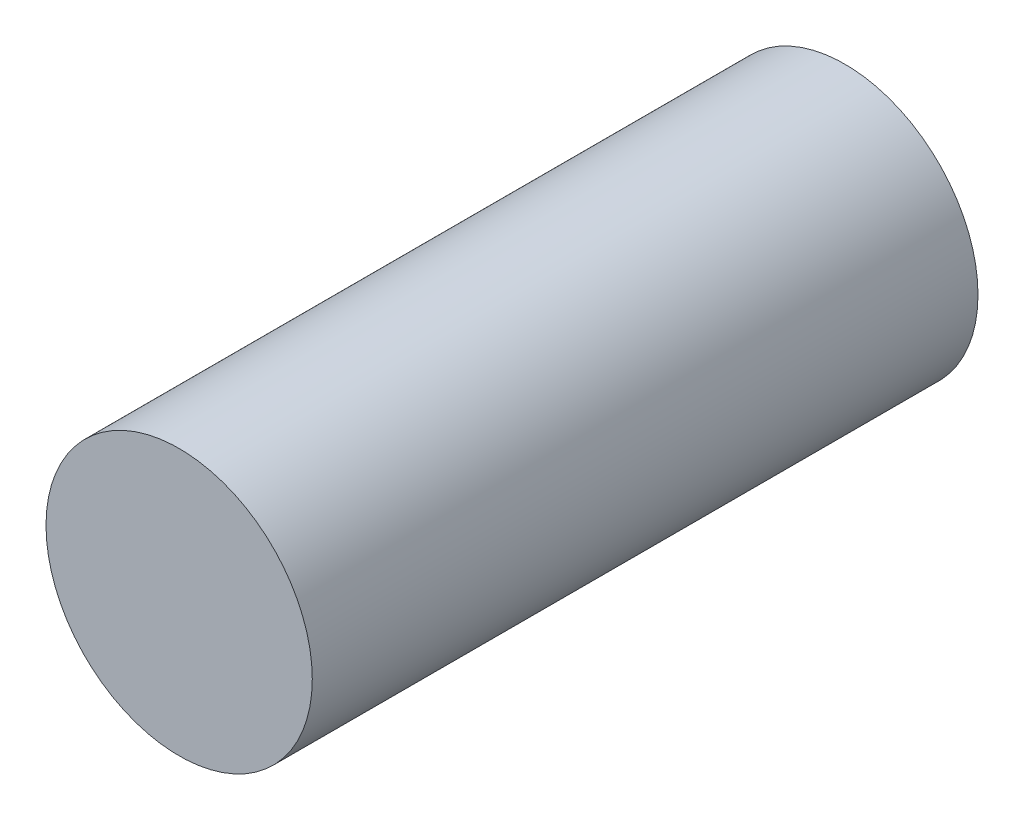
SolidWorks part; units mm, degrees
ref_plane "Plano frontal" through (0, 0, 0) normal (0, 0, 1) x (1, 0, 0)
ref_plane "Plano superior" through (0, 0, 0) normal (0, 1, 0) x (1, 0, 0)
ref_plane "Plano direito" through (0, 0, 0) normal (1, 0, 0) x (0, 0, -1)
sketch "Esboço1" plane through (0, 0, 0) normal (0, 0, 1) x (1, 0, 0)
  circle A0 centre (0, 0) radius 8
  dimension "D1" = 16
extrude "Ressalto-extrusão1" add sketch "Esboço1" along normal blind 40
